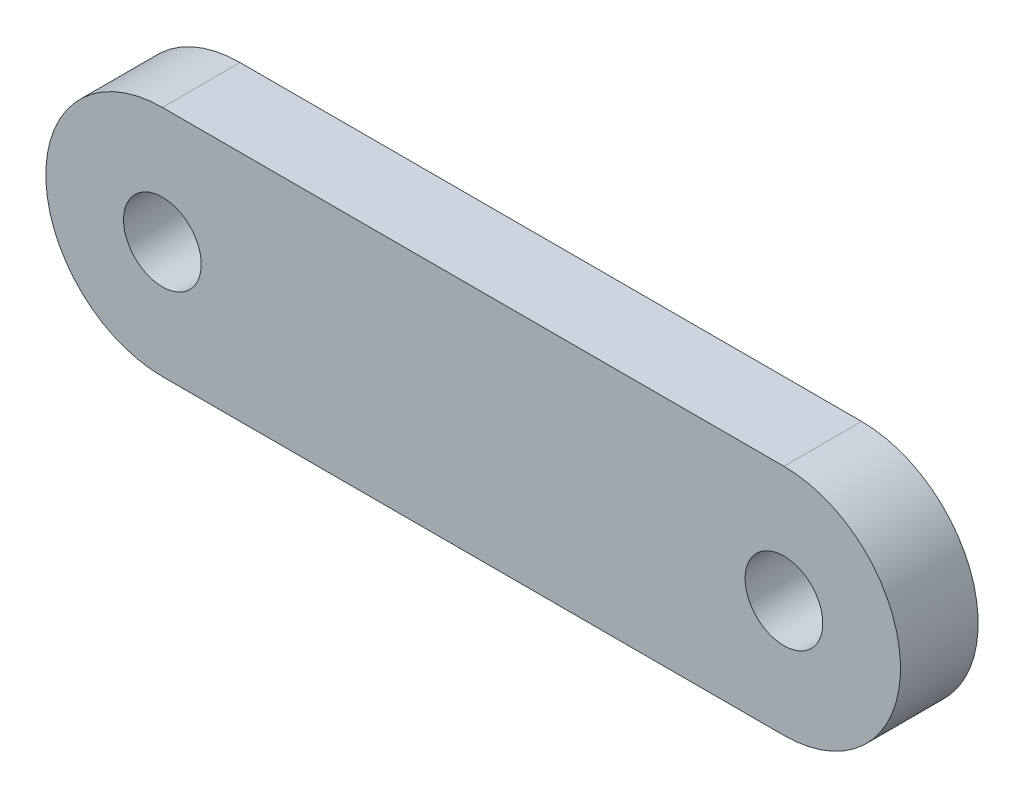
SolidWorks part; units mm, degrees
material "Nylon 6/10"
ref_plane "Front Plane" through (0, 0, 0) normal (0, 0, 1) x (1, 0, 0)
ref_plane "Top Plane" through (0, 0, 0) normal (0, 1, 0) x (1, 0, 0)
ref_plane "Right Plane" through (0, 0, 0) normal (1, 0, 0) x (0, 0, -1)
sketch "Sketch1" plane through (0, 0, 0) normal (0, 0, 1) x (1, 0, 0)
  line L0 (0, 4.7625) -> (25.4, 4.7625)
  line L1 (0, -4.7625) -> (25.4, -4.7625)
  circle A0 centre (0, 0) radius 1.5875
  circle A1 centre (25.4, 0) radius 1.5875
  circle A2 centre (0, 0) radius 4.7625
  circle A3 centre (25.4, 0) radius 4.7625
  dimension "D1" = 25.4
  dimension "D2" = 3.175
  dimension "D3" = 9.525
extrude "Boss-Extrude1" add sketch "Sketch1" along normal blind 3.175 contours A3 L0 A2 L1 | A2 A0 | A3 A1
